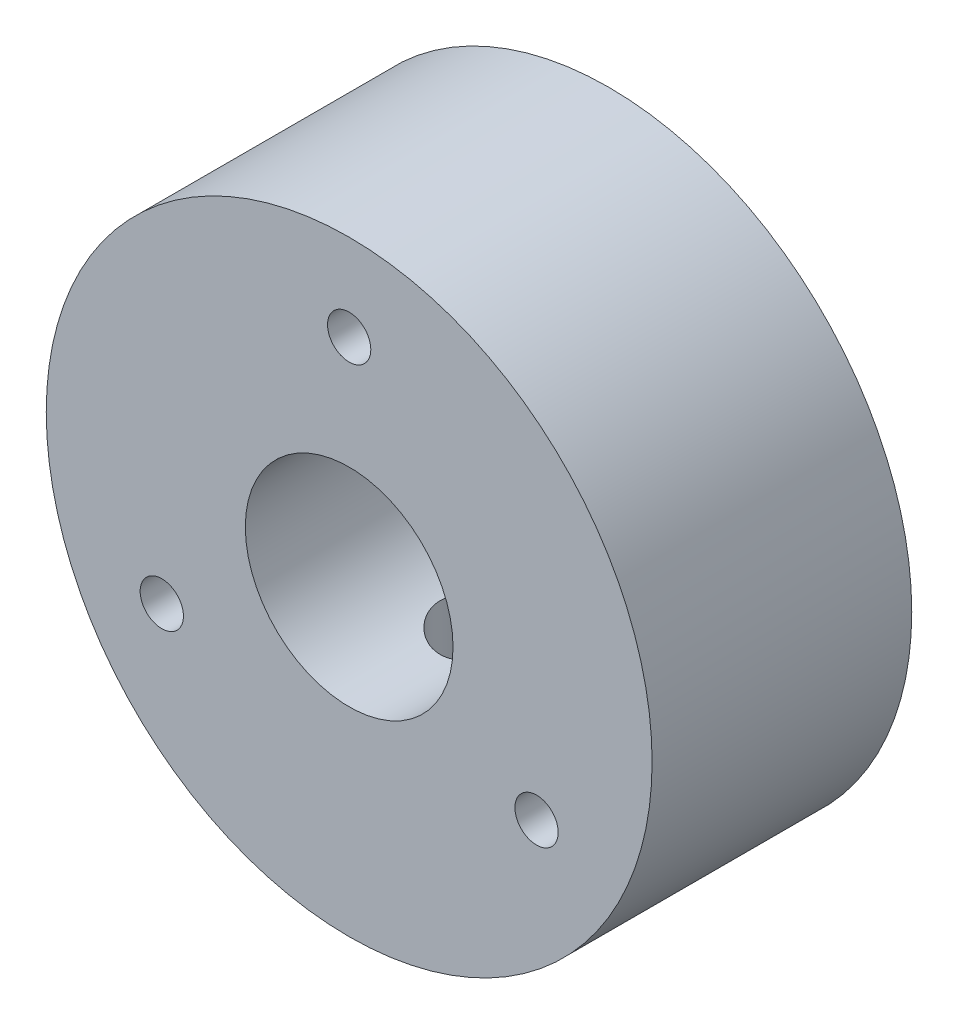
SolidWorks part; units mm, degrees
ref_plane "Front Plane" through (0, 0, 0) normal (0, 0, 1) x (1, 0, 0)
ref_plane "Top Plane" through (0, 0, 0) normal (0, 1, 0) x (1, 0, 0)
ref_plane "Right Plane" through (0, 0, 0) normal (1, 0, 0) x (0, 0, -1)
sketch "Sketch1" plane through (0, 0, 0) normal (0, 0, 1) x (1, 0, 0)
  circle A0 centre (0, 0) radius 6
  circle A1 centre (0, 0) radius 17.5
  dimension "D1" = 12
  dimension "D2" = 35
extrude "Boss-Extrude1" add sketch "Sketch1" along normal blind 15
sketch "Sketch2" plane through (0, 0, 0) normal (0, 1, 0) x (1, 0, 0)
  line L0 (0, 0) -> (0, -17.3639) construction
  line L1 (17.5, 0) -> (-17.5, 0) construction
  circle A0 centre (0, -7.5) radius 2.25
  dimension "D1" = 4.5
  dimension "D2" = 7.5
extrude "Cut-Extrude1" cut sketch "Sketch2" against normal through all
sketch "Sketch3" plane through (0, 0, 15) normal (0, 0, 1) x (1, 0, 0)
  line L0 (0, 0) -> (0, 18.2783) construction
  line L1 (0, 0) -> (19.6785, -11.3614) construction
  line L2 (0, 0) -> (-20.1486, -11.6328) construction
  circle A0 centre (0, 0) radius 12.5 construction
  circle A1 centre (0, 12.5) radius 1.25
  circle A2 centre (10.8253, -6.25) radius 1.25
  circle A3 centre (-10.8253, -6.25) radius 1.25
  dimension "D3" = 25
  dimension "D4" = 2.5
  dimension "D5" = 2.5
  dimension "D6" = 2.5
  dimension "D1" = 120
  dimension "D2" = 120
extrude "Cut-Extrude2" cut sketch "Sketch3" against normal through all
equation "\"D6@Sketch3\"=\"D4@Sketch3\""
equation "\"D5@Sketch3\"=\"D4@Sketch3\""
